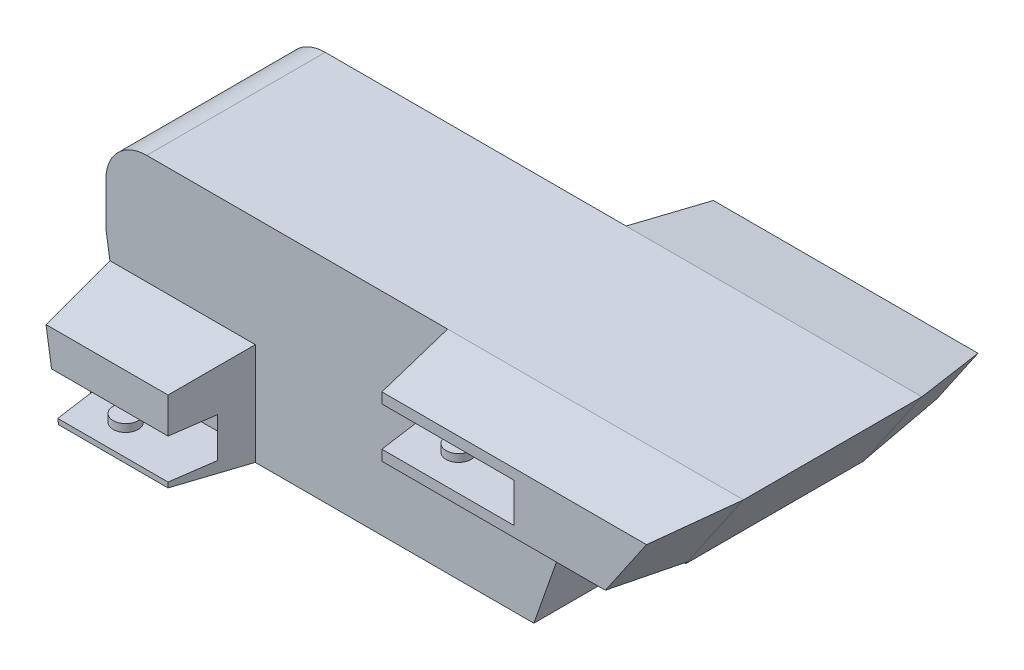
SolidWorks part; units mm, degrees
ref_plane "Alzado" through (0, 0, 0) normal (0, 0, 1) x (1, 0, 0)
ref_plane "Planta" through (0, 0, 0) normal (0, 1, 0) x (1, 0, 0)
ref_plane "Vista lateral" through (0, 0, 0) normal (1, 0, 0) x (0, 0, -1)
sketch "Croquis2" plane through (0, 0, 0) normal (0, 0, 1) x (1, 0, 0)
  line L1 (30.8779, -17.11) -> (39.6671, 7.89)
  line L2 (-53.0303, 7.89) -> (60.6671, 7.89) construction
  line L5 (71.9697, 24.39) -> (-45.0303, 24.39)
  line L6 (-53.0303, 7.89) -> (-53.0303, 16.39)
  line L7 (0, 0) -> (-53.0303, 24.39) construction
  line L8 (71.9697, 24.39) -> (0, 0) construction
  line L9 (39.6671, 7.89) -> (60.6671, 7.89)
  line L10 (60.6671, 7.89) -> (71.9697, 24.39)
  line L11 (30.8779, -17.11) -> (-49.1221, -17.11)
  line L12 (-49.1221, -17.11) -> (-53.0303, 7.89)
  arc A0 (-45.0303, 24.39) -> (-53.0303, 16.39) centre (-45.0303, 16.39) ccw
  point P5 (0, 0)
  dimension "D8" = 8
  dimension "D1" = 80
  dimension "D2" = 125
  dimension "D3" = 16.5
  dimension "D4" = 25
  dimension "D5" = 26.5
  dimension "D6" = 21
  dimension "D7" = 20
extrude "Saliente-Extruir1" add sketch "Croquis2" along normal blind 35
sketch "Croquis5" plane through (0, 0, 35) normal (0, 0, 1) x (1, 0, 0)
  line L0 (-53.0303, 7.89) -> (-49.1221, -17.11) construction
  line L1 (-49.1221, -17.11) -> (-23.7486, -17.11)
  line L3 (-52.2486, 2.89) -> (-23.7486, 2.89)
  line L4 (-23.7486, -17.11) -> (-23.7486, 2.89)
  line L5 (-49.1221, -17.11) -> (30.8779, -17.11) construction
  line L7 (-52.2486, 2.89) -> (-49.1221, -17.11)
  line L8 (60.6671, 7.89) -> (71.9697, 24.39) construction
  line L9 (71.9697, 24.39) -> (13.9697, 24.39)
  line L11 (61.0096, 8.39) -> (13.9697, 8.39)
  line L12 (13.9697, 24.39) -> (13.9697, 8.39)
  line L13 (71.9697, 24.39) -> (61.0096, 8.39)
  line L14 (39.6671, 7.89) -> (60.6671, 7.89) construction
  dimension "D1" = 20
  dimension "D2" = 28.5
  dimension "D3" = 0
  dimension "D4" = 0.5
  dimension "D5" = 58
extrude "Saliente-Extruir2" add sketch "Croquis5" along normal blind 15 draft 8
ref_plane "Plano1" through (0, 0, 17.5) normal (0, 0, -1) x (-1, 0, 0)
mirror "Simetría1" about plane through (0, 0, 17.5) normal (0, 0, -1) of "Saliente-Extruir2"
sketch "Croquis6" plane through (0, 0, -15) normal (0, 0, -1) x (-1, 0, 0)
  line L0 (51.017, 1.8359) -> (48.22, -16.056) construction
  line L1 (-13.9697, 20.2318) -> (-42.0241, 20.2318)
  line L2 (-13.9697, 20.2318) -> (-13.9697, 12.5481)
  line L3 (-13.9697, 12.5481) -> (-42.0241, 12.5481)
  line L4 (-42.0241, 20.2318) -> (-42.0241, 12.5481)
  line L5 (-42.0241, 22.2818) -> (-42.0241, 10.4981) construction
  line L6 (-67.9704, 22.2818) -> (-16.0779, 22.2818) construction
  line L7 (-16.0779, 10.4981) -> (-59.8984, 10.4981) construction
  line L8 (-13.9697, 24.39) -> (-13.9697, 8.39) construction
  line L9 (24.8027, 1.8359) -> (24.8027, -16.056) construction
  line L10 (25.8567, 0.7818) -> (23.7486, 2.89) construction
  line L11 (25.8567, -15.0019) -> (23.7486, -17.11) construction
  line L12 (49.7854, 0.7818) -> (52.2486, 2.89) construction
  line L13 (24.6605, -6.2019) -> (49.7605, -6.2019)
  line L14 (24.6605, -6.2019) -> (24.6605, -14.0019)
  line L15 (24.6605, -14.0019) -> (48.5411, -14.0019)
  line L17 (47.318, -15.0019) -> (49.1221, -17.11) construction
  line L18 (49.7605, -6.2019) -> (48.5411, -14.0019)
  line L19 (47.318, -15.0019) -> (25.8567, -15.0019) construction
  dimension "D1" = 2.05
  dimension "D2" = 2.05
  dimension "D3" = 1
  dimension "D4" = 7.8
  dimension "D5" = 25.1
extrude "Cortar-Extruir2" cut sketch "Croquis6" against normal blind 13.5
mirror "Simetría2" about plane through (0, 0, 17.5) normal (0, 0, -1) of "Cortar-Extruir2"
sketch "Croquis8" plane through (0, 20.2318, 0) normal (0, -1, 0) x (1, 0, 0)
  line L0 (16.0779, 50) -> (59.8984, 50) construction
  line L1 (16.0779, 50) -> (13.9697, 35) construction
  circle A0 centre (24.1825, 43) radius 2.45
  dimension "D1" = 4.9
  dimension "D2" = 7
  dimension "D3" = 9
extrude "Saliente-Extruir3" add sketch "Croquis8" along normal blind 1.5
mirror "Simetría3" about plane through (0, 0, 17.5) normal (0, 0, -1) of "Saliente-Extruir3"
sketch "Croquis9" plane through (0, 12.5481, 0) normal (0, 1, 0) x (1, 0, 0)
  line L0 (14.1805, -36.5) -> (16.0779, -50) construction
  line L1 (42.0241, -50) -> (16.0779, -50) construction
  circle A0 centre (24.1257, -43) radius 2.45
  point P4 (15.1292, -43.25)
  dimension "D1" = 4.9
  dimension "D2" = 9
  dimension "D3" = 7
extrude "Saliente-Extruir4" add sketch "Croquis9" along normal blind 1.5
mirror "Simetría4" about plane through (0, 0, 17.5) normal (0, 0, -1) of "Saliente-Extruir4"
sketch "Croquis10" plane through (0, -6.2019, 0) normal (0, -1, 0) x (1, 0, 0)
  line L0 (-25.8567, 50) -> (-23.7486, 35) construction
  line L1 (-48.6936, 50) -> (-25.8567, 50) construction
  circle A0 centre (-40.1609, 44) radius 2.45
  dimension "D1" = 4.9
  dimension "D2" = 15
  dimension "D3" = 6
extrude "Saliente-Extruir5" add sketch "Croquis10" along normal blind 1.5
mirror "Simetría5" about plane through (0, 0, 17.5) normal (0, 0, -1) of "Saliente-Extruir5"
sketch "Croquis13" plane through (0, -14.0019, 0) normal (0, 1, 0) x (1, 0, 0)
  line L0 (-25.8567, -50) -> (-23.7486, -35) construction
  line L1 (-25.8567, -50) -> (-47.4743, -50) construction
  circle A0 centre (-40.1609, -44) radius 2.45
  dimension "D1" = 4.9
  dimension "D2" = 15
  dimension "D3" = 6
extrude "Saliente-Extruir6" add sketch "Croquis13" along normal blind 1.5
mirror "Simetría6" about plane through (0, 0, 17.5) normal (0, 0, -1) of "Saliente-Extruir6"
